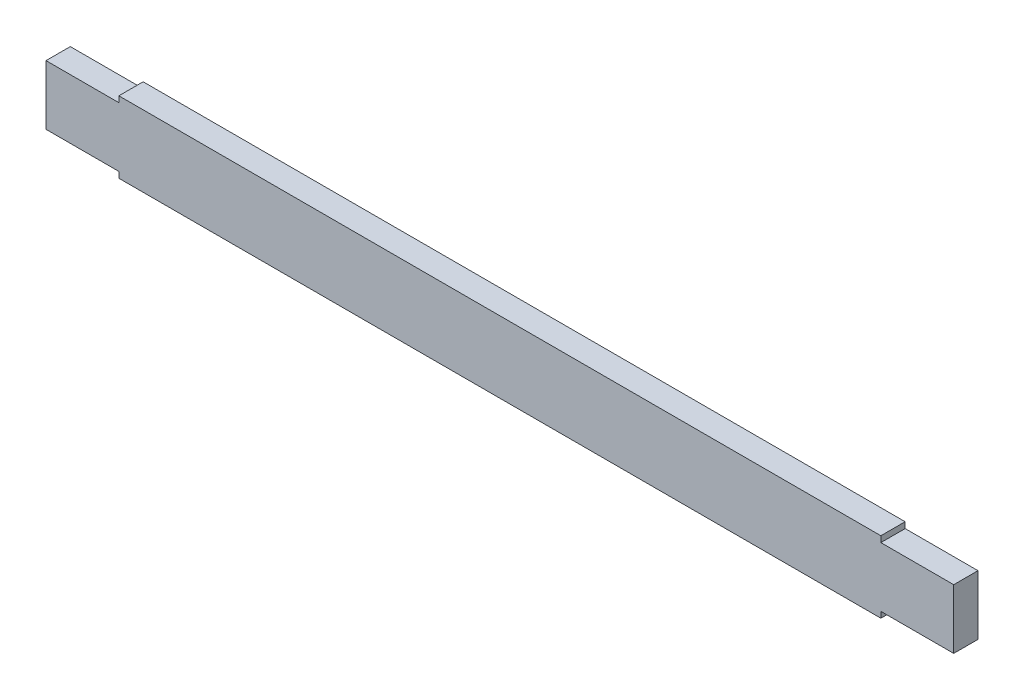
SolidWorks part; units mm, degrees
ref_plane "Front Plane" through (0, 0, 0) normal (0, 0, 1) x (1, 0, 0)
ref_plane "Top Plane" through (0, 0, 0) normal (0, 1, 0) x (1, 0, 0)
ref_plane "Right Plane" through (0, 0, 0) normal (1, 0, 0) x (0, 0, -1)
sketch "Sketch1" plane through (0, 0, 0) normal (0, 0, 1) x (1, 0, 0)
  line L0 (-80, 6.25) -> (-80, 7.5)
  line L1 (80, -7.5) -> (-80, -7.5)
  line L2 (80, -7.5) -> (80, -6.25)
  line L3 (80, 7.5) -> (-80, 7.5)
  line L4 (-80, -7.5) -> (-80, -6.25)
  line L5 (80, -7.5) -> (-80, 7.5) construction
  line L6 (80, 7.5) -> (-80, -7.5) construction
  line L7 (-80, 6.25) -> (-95.3, 6.25)
  line L9 (-80, -6.25) -> (-95.3, -6.25)
  line L10 (-95.3, 6.25) -> (-95.3, -6.25)
  line L11 (80, 6.25) -> (95.3, 6.25)
  line L13 (80, -6.25) -> (95.3, -6.25)
  line L14 (95.3, 6.25) -> (95.3, -6.25)
  line L15 (80, 6.25) -> (80, 7.5)
  point P0 (0, 0)
  point P14 (-95.3, 0)
  point P15 (95.3, 0)
  dimension "D1" = 160
  dimension "D2" = 15.3
  dimension "D3" = 15.3
  dimension "D4" = 12.5
  dimension "D5" = 12.5
  dimension "D6" = 15
extrude "Boss-Extrude2" add sketch "Sketch1" along normal blind 5.1
